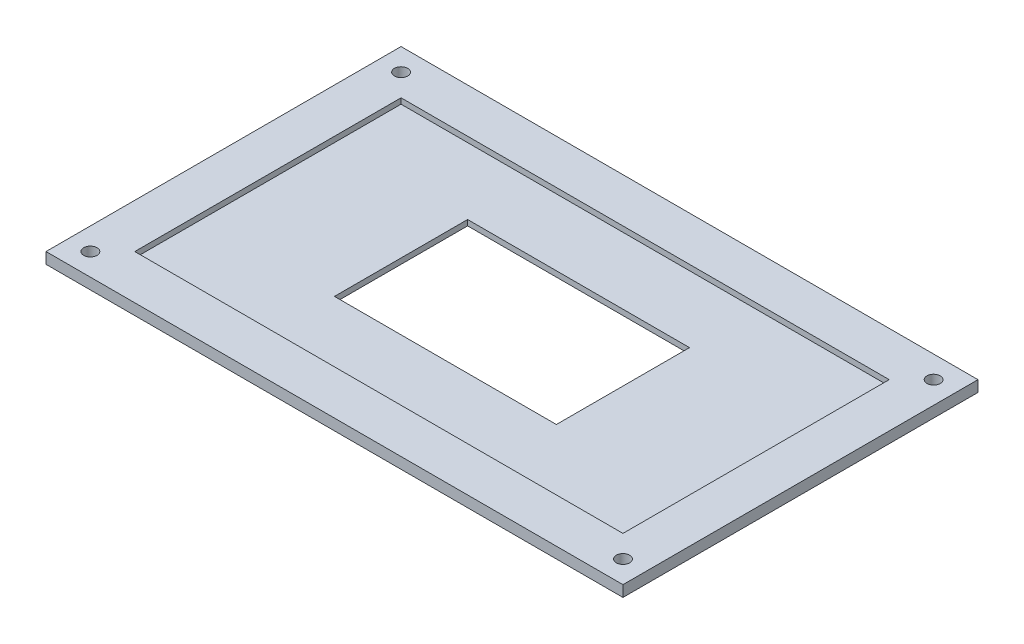
SolidWorks part; units mm, degrees
material "ABS PC"
ref_plane "Front Plane" through (0, 0, 0) normal (0, 0, 1) x (1, 0, 0)
ref_plane "Top Plane" through (0, 0, 0) normal (0, 1, 0) x (1, 0, 0)
ref_plane "Right Plane" through (0, 0, 0) normal (1, 0, 0) x (0, 0, -1)
sketch "Sketch1" plane through (0, 0, 0) normal (0, 1, 0) x (1, 0, 0)
  line L1 (0, 0) -> (130, 0)
  line L2 (0, 0) -> (0, 80)
  line L3 (0, 80) -> (130, 80)
  line L4 (130, 0) -> (130, 80)
  dimension "D1" = 130
  dimension "D2" = 80
extrude "Boss-Extrude1" add sketch "Sketch1" along normal blind 2.5
sketch "Sketch2" plane through (0, 2.5, 0) normal (0, 1, 0) x (1, 0, 0)
  line L0 (0, 80) -> (0, 0) construction
  line L1 (10, 70) -> (120, 70)
  line L2 (10, 70) -> (10, 10)
  line L3 (10, 10) -> (120, 10)
  line L4 (120, 70) -> (120, 10)
  line L5 (130, 0) -> (130, 80) construction
  line L6 (130, 80) -> (0, 80) construction
  line L7 (0, 0) -> (130, 0) construction
  dimension "D1" = 10
  dimension "D2" = 10
  dimension "D3" = 10
  dimension "D4" = 10
extrude "Cut-Extrude1" cut sketch "Sketch2" against normal blind 1.25
sketch "Sketch3" plane through (0, 2.5, 0) normal (0, 1, 0) x (1, 0, 0)
  line L0 (0, 80) -> (0, 0) construction
  line L1 (130, 80) -> (0, 80) construction
  line L2 (0, 0) -> (130, 0) construction
  line L3 (130, 0) -> (130, 80) construction
  circle A0 centre (5, 75) radius 1.5
  circle A1 centre (125, 75) radius 1.5
  circle A2 centre (125, 5) radius 1.5
  circle A3 centre (5, 5) radius 1.5
  dimension "D1" = 3
  dimension "D2" = 5
  dimension "D3" = 5
  dimension "D4" = 5
  dimension "D5" = 5
extrude "Cut-Extrude2" cut sketch "Sketch3" against normal through all
sketch "Sketch4" plane through (0, 1.25, 0) normal (0, 1, 0) x (1, 0, 0)
  line L0 (120, 70) -> (10, 70) construction
  line L1 (40, 55) -> (90, 55)
  line L2 (40, 55) -> (40, 25)
  line L3 (40, 25) -> (90, 25)
  line L4 (90, 55) -> (90, 25)
  line L6 (10, 70) -> (10, 10) construction
  dimension "D1" = 30
  dimension "D2" = 50
  dimension "D3" = 15
  dimension "D4" = 30
extrude "Cut-Extrude3" cut sketch "Sketch4" against normal through all
